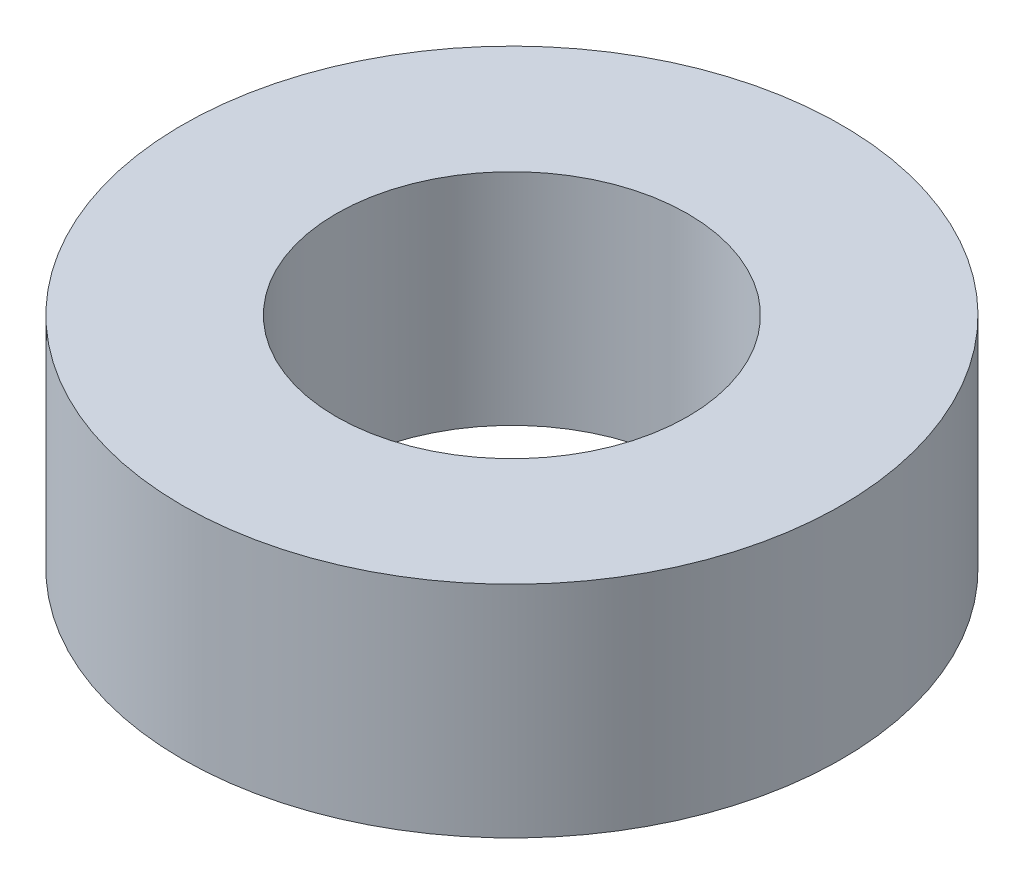
SolidWorks part; units mm, degrees
ref_plane "Front Plane" through (0, 0, 0) normal (0, 0, 1) x (1, 0, 0)
ref_plane "Top Plane" through (0, 0, 0) normal (0, 1, 0) x (1, 0, 0)
ref_plane "Right Plane" through (0, 0, 0) normal (1, 0, 0) x (0, 0, -1)
sketch "Sketch3" plane through (0, 0, 0) normal (0, 1, 0) x (1, 0, 0)
  circle A0 centre (0, 0) radius 7.62
extrude "Boss-Extrude1" add sketch "Sketch3" along normal blind 5.08
sketch "Sketch4" plane through (0, 5.08, 0) normal (0, 1, 0) x (1, 0, 0)
  circle A0 centre (0, 0) radius 4.064
extrude "Cut-Extrude1" cut sketch "Sketch4" against normal blind 5.08
